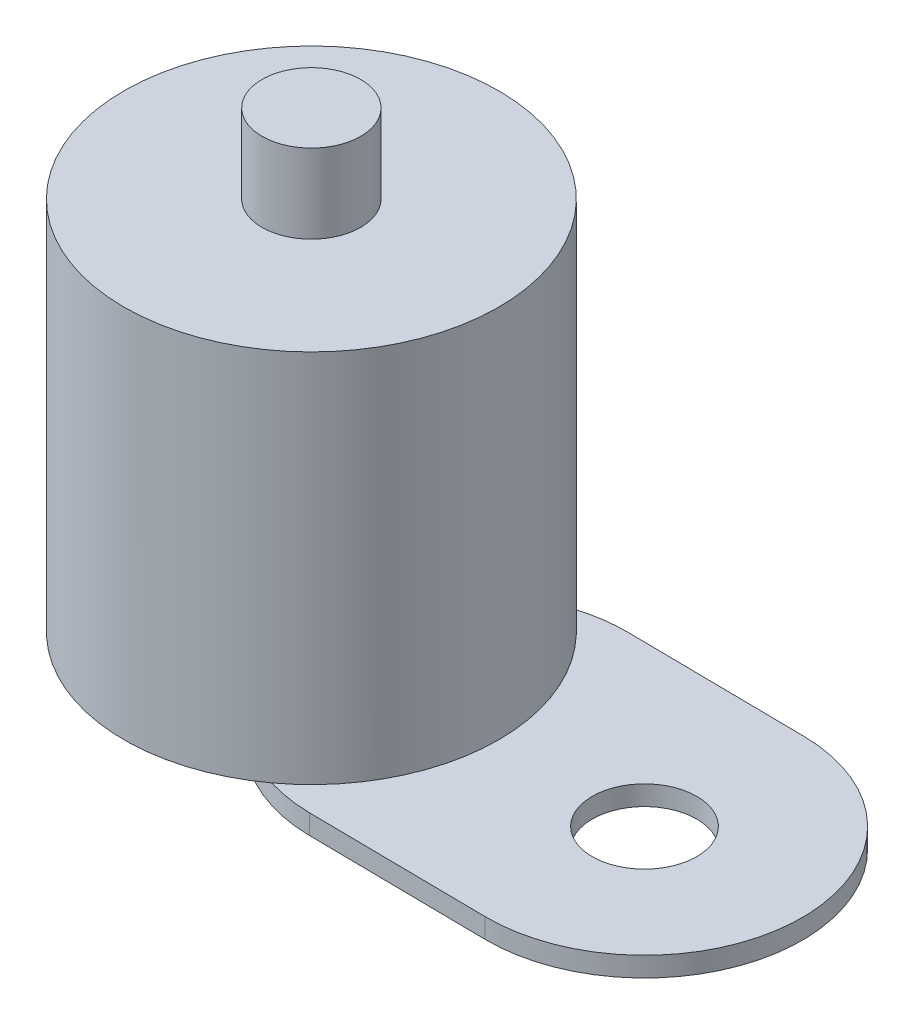
SolidWorks part; units mm, degrees
ref_plane "Front Plane" through (0, 0, 0) normal (0, 0, 1) x (1, 0, 0)
ref_plane "Top Plane" through (0, 0, 0) normal (0, 1, 0) x (1, 0, 0)
ref_plane "Right Plane" through (0, 0, 0) normal (1, 0, 0) x (0, 0, -1)
sketch "Sketch1" plane through (0, 0, 0) normal (0, 1, 0) x (1, 0, 0)
  circle A0 centre (0, 0) radius 9.5
  circle A1 centre (0, 0) radius 2.5
  dimension "D1" = 19
  dimension "D2" = 5
extrude "Boss-Extrude1" add sketch "Sketch1" along normal blind 19 contours A1 | A0 A1
sketch "Sketch2" plane through (0, 19, 0) normal (0, 1, 0) x (1, 0, 0)
  circle A1 centre (0, 0) radius 2.5
  circle A2 centre (0, 0) radius 2.5
  dimension "D1" = 0
extrude "Boss-Extrude2" add sketch "Sketch2" along normal blind 4
sketch "Sketch3" plane through (0, 0, 0) normal (0, -1, 0) x (1, 0, 0)
  line L0 (8, 0) -> (17, 0.1091) construction
  line L1 (7.903, 7.9994) -> (16.903, 8.1085)
  line L2 (8.097, -7.9994) -> (17.097, -7.8903)
  arc A0 (7.903, 7.9994) -> (8.097, -7.9994) centre (8, 0) ccw
  arc A1 (17.097, -7.8903) -> (16.903, 8.1085) centre (17, 0.1091) ccw
  circle A2 centre (0, 0) radius 9.5 construction
  circle A3 centre (17, 0.1091) radius 2.65
  point P2 (12.5, 0.0545)
  dimension "D2" = 15.5
  dimension "D3" = 5.3
  dimension "D1" = 16
extrude "Boss-Extrude3" add sketch "Sketch3" along normal blind 1
